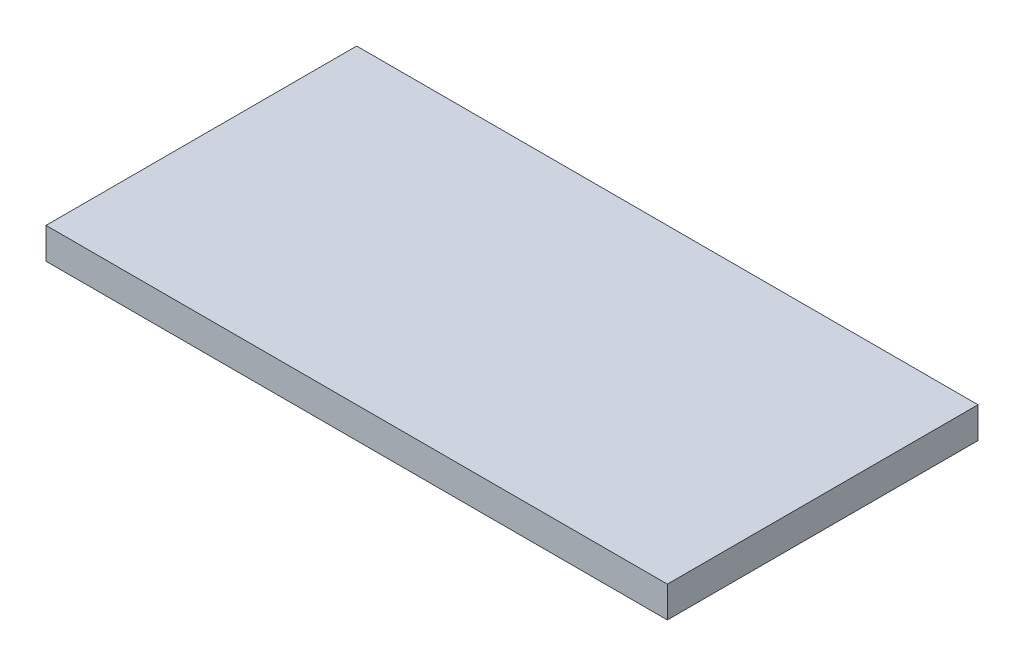
SolidWorks part; units mm, degrees
ref_plane "Front Plane" through (0, 0, 0) normal (0, 0, 1) x (1, 0, 0)
ref_plane "Top Plane" through (0, 0, 0) normal (0, 1, 0) x (1, 0, 0)
ref_plane "Right Plane" through (0, 0, 0) normal (1, 0, 0) x (0, 0, -1)
sketch "Sketch2" plane through (0, 0, 0) normal (0, 1, 0) x (1, 0, 0)
  line L1 (-63.5, 31.75) -> (63.5, 31.75)
  line L2 (-63.5, 31.75) -> (-63.5, -31.75)
  line L3 (-63.5, -31.75) -> (63.5, -31.75)
  line L4 (63.5, 31.75) -> (63.5, -31.75)
  line L5 (-63.5, 31.75) -> (63.5, -31.75) construction
  line L6 (-63.5, -31.75) -> (63.5, 31.75) construction
  point P0 (0, 0)
  dimension "D1" = 63.5
  dimension "D2" = 127
extrude "Boss-Extrude1" add sketch "Sketch2" along normal blind 6.35
